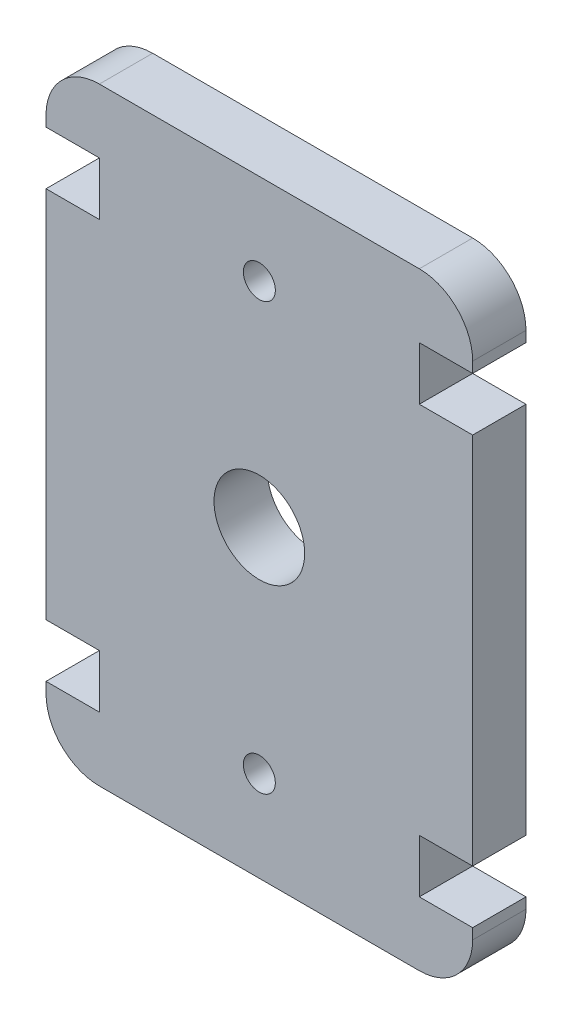
SolidWorks part; units mm, degrees
ref_plane "Plan de face" through (0, 0, 0) normal (0, 0, 1) x (1, 0, 0)
ref_plane "Plan de dessus" through (0, 0, 0) normal (0, 1, 0) x (1, 0, 0)
ref_plane "Plan de droite" through (0, 0, 0) normal (1, 0, 0) x (0, 0, -1)
sketch "Esquisse1" plane through (0, 0, 0) normal (0, 0, 1) x (1, 0, 0)
  line L0 (-20, 0) -> (20, 0)
  line L1 (20, 0) -> (20, 6)
  line L2 (20, 6) -> (15, 6)
  line L3 (15, 6) -> (15, 11)
  line L4 (15, 11) -> (20, 11)
  line L5 (20, 11) -> (20, 46)
  line L6 (20, 46) -> (15, 46)
  line L7 (15, 46) -> (15, 51)
  line L8 (15, 51) -> (20, 51)
  line L9 (20, 51) -> (20, 57)
  line L10 (20, 57) -> (-20, 57)
  line L11 (-20, 57) -> (-20, 51) construction
  line L12 (-20, 51) -> (-15, 51)
  line L13 (-15, 51) -> (-15, 46)
  line L14 (-15, 46) -> (-20, 46)
  line L15 (-20, 46) -> (-20, 11) construction
  line L16 (-20, 11) -> (-15, 11)
  line L17 (-15, 11) -> (-15, 6)
  line L18 (-15, 6) -> (-20, 6)
  line L19 (-20, 6) -> (-20, 0) construction
  line L20 (0, 0) -> (0, 57) construction
  line L21 (-15, 8.5) -> (15, 8.5) construction
  line L22 (15, 48.5) -> (-15, 48.5) construction
  line L23 (-20, 28.5) -> (20, 28.5) construction
  line L25 (-20, 57) -> (-20, 51)
  line L26 (-20, 46) -> (-20, 11)
  line L27 (-20, 6) -> (-20, 0)
  circle A0 centre (0, 48.5) radius 1.5
  circle A1 centre (0, 8.5) radius 1.5
  circle A2 centre (0, 28.5) radius 4.25
  circle A3 centre (-20, 28.5) radius 1.6 construction
  circle A4 centre (20, 28.5) radius 1.6 construction
  dimension "D6" = 3
  dimension "D7" = 3
  dimension "D8" = 8.5
  dimension "D10" = 3.2
  dimension "D1" = 5
  dimension "D2" = 30
  dimension "D3" = 40
  dimension "D9" = 40
  dimension "D11" = 20
extrude "Boss.-Extru.1" add sketch "Esquisse1" along normal blind 5
fillet "Congé1" radius 5 4 edges at (20, 57, 2.5) (20, 0, 2.5) (-20, 0, 2.5) (-20, 57, 2.5)
